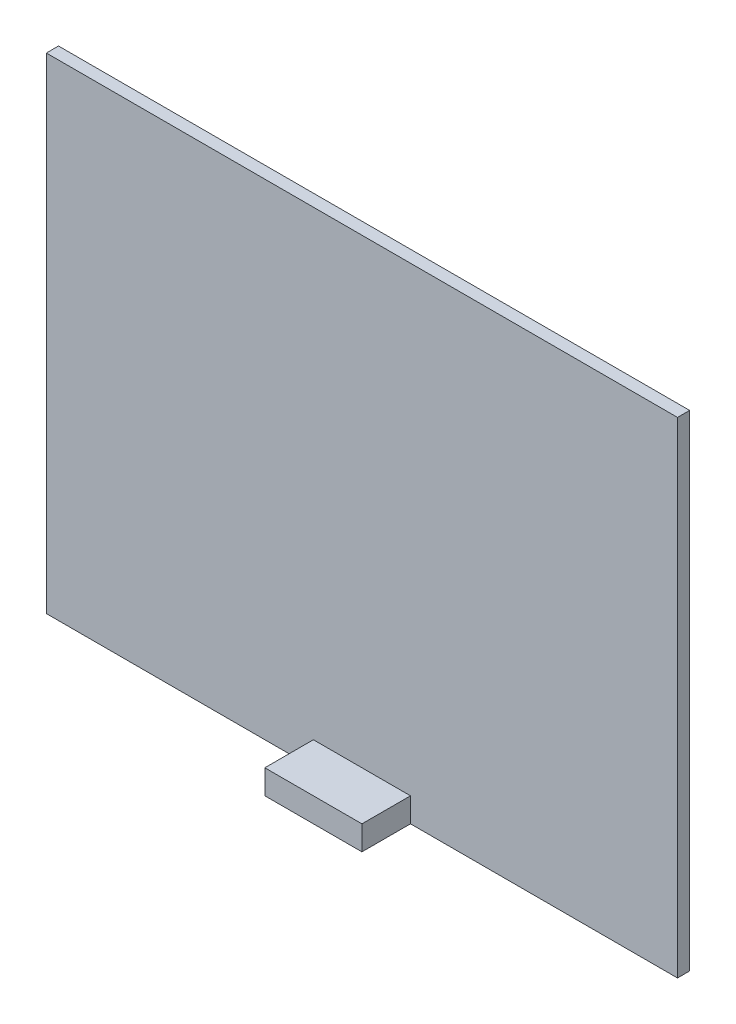
SolidWorks part; units mm, degrees
ref_plane "Front Plane" through (0, 0, 0) normal (0, 0, 1) x (1, 0, 0)
ref_plane "Top Plane" through (0, 0, 0) normal (0, 1, 0) x (1, 0, 0)
ref_plane "Right Plane" through (0, 0, 0) normal (1, 0, 0) x (0, 0, -1)
sketch "Sketch1" plane through (0, 0, 0) normal (0, 0, 1) x (1, 0, 0)
  line L1 (-150, 100) -> (150, 100)
  line L2 (-150, 100) -> (-150, -100)
  line L3 (-150, -100) -> (150, -100)
  line L4 (150, 100) -> (150, -100)
  line L5 (-150, 100) -> (150, -100) construction
  line L6 (-150, -100) -> (150, 100) construction
  point P0 (0, 0)
  dimension "D1" = 300
  dimension "D2" = 200
extrude "Boss-Extrude1" add sketch "Sketch1" along normal blind 5
sketch "Sketch3" plane through (0, 0, 5) normal (0, 0, 1) x (1, 0, 0)
  line L1 (-150, -100) -> (-130, -100)
  line L2 (-150, -100) -> (-150, -80)
  line L3 (-150, -80) -> (-130, -80)
  line L4 (-130, -100) -> (-130, -80)
  line L5 (-150, 100) -> (-130, 100)
  line L6 (-150, 100) -> (-150, 60)
  line L7 (-150, 60) -> (-130, 60)
  line L8 (-130, 100) -> (-130, 60)
  line L9 (150, 100) -> (130, 100)
  line L10 (150, 100) -> (150, 60)
  line L11 (150, 60) -> (130, 60)
  line L12 (130, 100) -> (130, 60)
  line L13 (150, -100) -> (130, -100)
  line L14 (150, -100) -> (150, -80)
  line L15 (150, -80) -> (130, -80)
  line L16 (130, -100) -> (130, -80)
  dimension "D1" = 20
  dimension "D2" = 20
  dimension "D3" = 40
extrude "Cut-Extrude1" cut sketch "Sketch3" against normal blind 5
sketch "Sketch4" plane through (0, 0, 5) normal (0, 0, 1) x (1, 0, 0)
  line L1 (-150, 60) -> (-130, 60)
  line L2 (-150, 60) -> (-150, -80)
  line L3 (-150, -80) -> (-130, -80)
  line L4 (-130, 60) -> (-130, -80)
  line L5 (130, 60) -> (150, 60)
  line L6 (130, 60) -> (130, -80)
  line L7 (130, -80) -> (150, -80)
  line L8 (150, 60) -> (150, -80)
extrude "Cut-Extrude2" cut sketch "Sketch4" against normal blind 10
sketch "Sketch6" plane through (0, -100, 0) normal (0, -1, 0) x (1, 0, 0)
  line L0 (-130, 0) -> (130, 0) construction
  line L1 (-20, 25) -> (20, 25)
  line L2 (-20, 25) -> (-20, 0)
  line L3 (-20, 0) -> (20, 0)
  line L4 (20, 25) -> (20, 0)
  line L5 (-130, 0) -> (-130, 5) construction
  line L6 (130, 0) -> (130, 5) construction
  dimension "D1" = 25
  dimension "D2" = 110
  dimension "D3" = 110
extrude "Boss-Extrude3" add sketch "Sketch6" against normal blind 10
